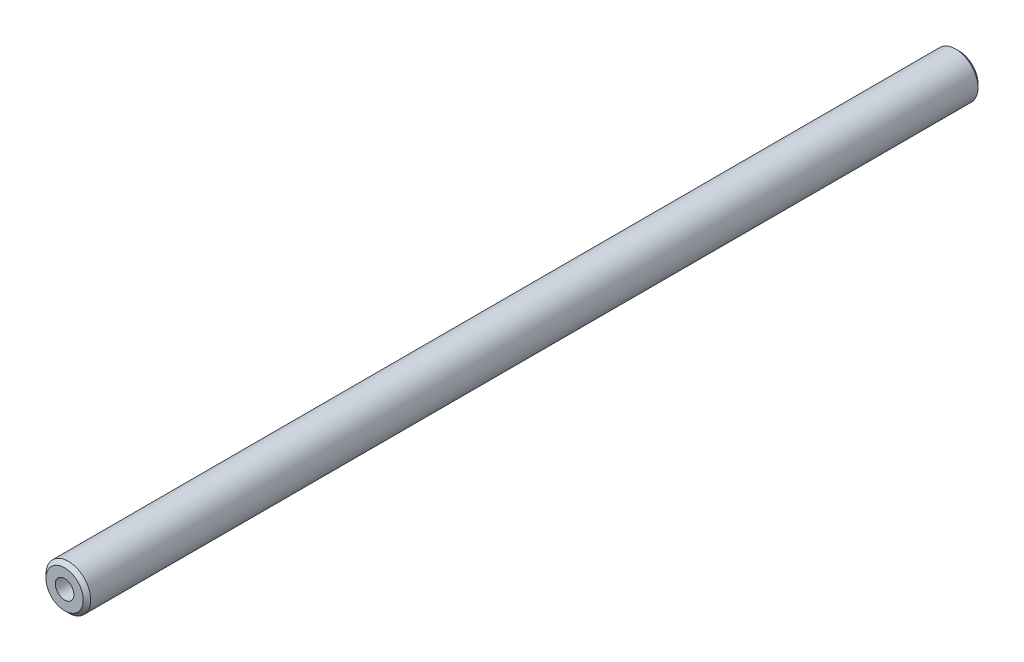
SolidWorks part; units mm, degrees
material "A2017"
ref_plane "正面" through (0, 0, 0) normal (0, 0, 1) x (1, 0, 0)
ref_plane "平面" through (0, 0, 0) normal (0, 1, 0) x (1, 0, 0)
ref_plane "右側面" through (0, 0, 0) normal (1, 0, 0) x (0, 0, -1)
sketch "ｽｹｯﾁ1" plane through (0, 0, 0) normal (0, 0, 1) x (1, 0, 0)
  circle A0 centre (0, 0) radius 3
  dimension "D1" = 6
extrude "ﾎﾞｽ - 押し出し1" add sketch "ｽｹｯﾁ1" along normal mid plane 120
chamfer "面取り1" distance 0.5 angle 45 2 edges at (3, 0, -60) (3, 0, 60)
hole_wizard "M3 ねじ穴1" positions "ｽｹｯﾁ2" profile "ｽｹｯﾁ3" tap size "M3" standard "JIS"
sketch "ｽｹｯﾁ2" plane through (0, 0, 60) normal (0, 0, 1) x (1, 0, 0)
  point P0 (0, 0)
sketch "ｽｹｯﾁ3" plane through (0, 0, 60) normal (1, 0, 0) x (0, -1, 0)
  line L0 (0, 0) -> (0, 9.2511)
  line L1 (0, 9.2511) -> (1.25, 8.5)
  line L2 (1.25, 8.5) -> (1.25, 0)
  line L5 (1.25, 0) -> (0, 0)
  line L10 (0, 9.2511) -> (-1.25, 8.5) construction
  line L11 (0, -6.35) -> (0, 107.95) construction
  dimension "ねじ下穴ﾄﾞﾘﾙ直径" = 2.5
  dimension "ねじ下穴ﾄﾞﾘﾙの深さ" = 8.5
  dimension "ﾄﾞﾘﾙ角度" = 118
cosmetic thread "穴のねじ山1" parameters "D1"=6, "D2"=3
mirror "ﾐﾗｰ1" about plane through (0, 0, 0) normal (0, 0, 1) of "M3 ねじ穴1"
